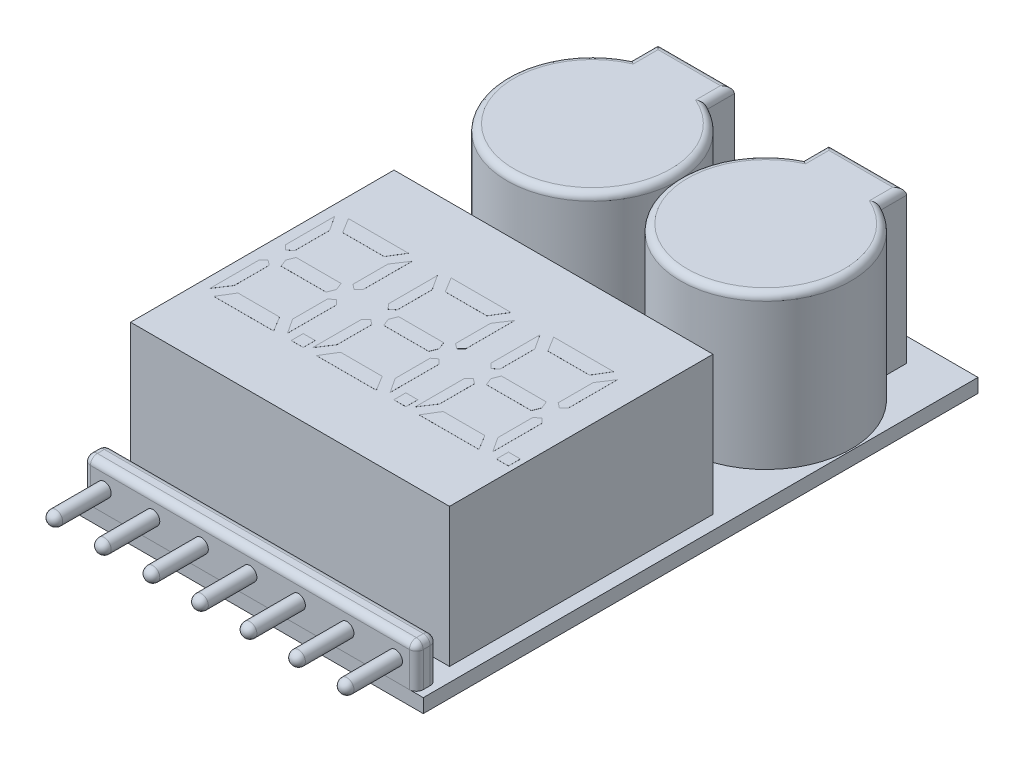
SolidWorks part; units mm, degrees
ref_plane "Ön Düzlem" through (0, 0, 0) normal (0, 0, 1) x (1, 0, 0)
ref_plane "Üst Düzlem" through (0, 0, 0) normal (0, 1, 0) x (1, 0, 0)
ref_plane "Sağ Düzlem" through (0, 0, 0) normal (1, 0, 0) x (0, 0, -1)
sketch "Çizim1" plane through (0, 0, 0) normal (0, 1, 0) x (1, 0, 0)
  line L1 (12.5, -20) -> (-12.5, -20)
  line L2 (12.5, -20) -> (12.5, 20)
  line L3 (12.5, 20) -> (-12.5, 20)
  line L4 (-12.5, -20) -> (-12.5, 20)
  line L5 (12.5, -20) -> (-12.5, 20) construction
  line L6 (12.5, 20) -> (-12.5, -20) construction
  point P0 (0, 0)
  dimension "D1" = 40
  dimension "D2" = 25
extrude "extruded boss" add sketch "Çizim1" along normal blind 1
sketch "Çizim2" plane through (0, 1, 0) normal (0, 1, 0) x (1, 0, 0)
  line L0 (-12.5, -20) -> (12.5, -20) construction
  line L1 (-12, -20) -> (12, -20)
  line L2 (-12, -20) -> (-12, -18.5)
  line L3 (-12, -18.5) -> (12, -18.5)
  line L4 (12, -20) -> (12, -18.5)
  line L5 (-12.5, 20) -> (-12.5, -20) construction
  line L6 (12.5, -20) -> (12.5, 20) construction
  dimension "D1" = 0.5
  dimension "D2" = 0.5
  dimension "D3" = 1.5
extrude "pin header" add sketch "Çizim2" along normal blind 3 separate body
sketch "Çizim3" plane through (0, 0, 20) normal (0, 0, 1) x (1, 0, 0)
  line L0 (-12, 2.5) -> (12, 2.5) construction
  line L1 (-12, 4) -> (-12, 1) construction
  line L2 (12, 4) -> (12, 1) construction
  line L3 (-8.5, 2.5) -> (15.5, 2.5) construction
  line L4 (-5, 2.5) -> (19, 2.5) construction
  line L5 (-1.5, 2.5) -> (22.5, 2.5) construction
  line L6 (-15.5, 2.5) -> (8.5, 2.5) construction
  line L7 (-19, 2.5) -> (5, 2.5) construction
  line L8 (-22.5, 2.5) -> (1.5, 2.5) construction
  circle A0 centre (0, 2.5) radius 0.5
  circle A1 centre (3.5, 2.5) radius 0.5
  circle A2 centre (7, 2.5) radius 0.5
  circle A3 centre (10.5, 2.5) radius 0.5
  circle A4 centre (-3.5, 2.5) radius 0.5
  circle A5 centre (-7, 2.5) radius 0.5
  circle A6 centre (-10.5, 2.5) radius 0.5
  dimension "D1" = 1
  dimension "D2" = 4
  dimension "D3" = 4
extrude "pins" add sketch "Çizim3" along normal blind 4
sketch "Çizim4" plane through (0, 1, 0) normal (0, 1, 0) x (1, 0, 0)
  line L1 (-11.5, -17.1093) -> (11.5, -17.1093)
  line L2 (-11.5, -17.1093) -> (-11.5, 1.8907)
  line L3 (-11.5, 1.8907) -> (11.5, 1.8907)
  line L4 (11.5, -17.1093) -> (11.5, 1.8907)
  line L5 (-11.5, -17.1093) -> (11.5, 1.8907) construction
  line L6 (-11.5, 1.8907) -> (11.5, -17.1093) construction
  point P0 (0, -7.6093)
  dimension "D1" = 19
  dimension "D2" = 23
extrude "display" add sketch "Çizim4" along normal blind 10
sketch "Çizim5" plane through (0, 1, 0) normal (0, 1, 0) x (1, 0, 0)
  line L7 (3.4483, 16.4277) -> (3.4483, 18.2977)
  line L9 (-9, 16.4539) -> (-9, 18.4278)
  line L10 (-9, 18.4278) -> (-3.5, 18.4278)
  line L11 (-3.5, 16.4539) -> (-3.5, 18.4278)
  line L14 (9.0517, 18.2977) -> (3.4483, 18.2977)
  line L15 (9.0517, 16.4277) -> (9.0517, 18.2977)
  arc A0 (-9, 16.4539) -> (-3.5, 16.4539) centre (-6.25, 10.9454) ccw
  arc A1 (3.4483, 16.4277) -> (9.0517, 16.4277) centre (6.25, 10.9454) ccw
  point P9 (0, 6.418)
  point P16 (-6.25, 17.1022)
  dimension "D1" = 5.5
extrude "buzzer" add sketch "Çizim5" along normal blind 11
fillet "fillet 1" radius 0.5 8 edges at (12, 4, 19.25) (0, 4, 20) (12, 2.5, 20) (-12, 4, 19.25) (-12, 2.5, 20) (-12, 2.5, 18.5) (0, 4, 18.5) (12, 2.5, 18.5)
fillet "fillet 2" radius 0.5 8 edges at (3.4483, 12, -17.3627) (6.25, 12, -18.2977) (9.0517, 12, -17.3627) (6.25, 12, -4.7885) (-9, 12, -17.4408) (-6.25, 12, -18.4278) (-3.5, 12, -17.4408) (-6.25, 12, -4.7885)
sketch "Çizim8" plane through (0, 11, 0) normal (0, 1, 0) x (1, 0, 0)
  line L0 (-9.5659, -7.1026) -> (-6.3259, -7.1026)
  line L1 (-6.4462, -11.4175) -> (-9.4456, -11.4175)
  line L2 (-9.4456, -11.4175) -> (-10.1059, -12.4975)
  line L3 (-10.048, -11.0796) -> (-10.743, -12.1376)
  line L4 (-10.743, -12.1376) -> (-10.743, -8.6075)
  line L5 (-10.048, -11.0796) -> (-10.048, -8.5587)
  line L6 (-10.743, -8.6075) -> (-10.4177, -8.2746)
  line L7 (-10.4177, -8.2746) -> (-10.048, -8.5587)
  line L8 (-9.5659, -8.1826) -> (-6.3259, -8.1826)
  line L9 (-10.1059, -12.4975) -> (-5.7859, -12.4975)
  line L10 (-4.559, -11.5993) -> (-3.695, -11.5993)
  line L11 (-4.559, -11.5993) -> (-4.559, -12.4633)
  line L12 (-4.559, -12.4633) -> (-3.695, -12.4633)
  line L13 (-9.7799, -7.6426) -> (-9.5659, -7.1026)
  line L14 (-3.695, -11.5993) -> (-3.695, -12.4633)
  line L15 (-6.112, -7.6426) -> (-6.3259, -7.1026)
  line L16 (-5.4741, -8.2746) -> (-5.8439, -8.5587)
  line L17 (-5.1489, -8.6075) -> (-5.4741, -8.2746)
  line L18 (-5.8439, -11.0796) -> (-5.8439, -8.5587)
  line L19 (-5.1489, -12.1376) -> (-5.1489, -8.6075)
  line L20 (-5.8439, -11.0796) -> (-5.1489, -12.1376)
  line L21 (-6.4462, -11.4175) -> (-5.7859, -12.4975)
  line L23 (-2.7059, -12.4975) -> (1.6141, -12.4975)
  line L24 (-5.7859, -2.7878) -> (-10.1059, -2.7878)
  line L25 (4.6941, -12.4975) -> (9.0141, -12.4975)
  line L26 (-9.4456, -3.8678) -> (-6.4462, -3.8678)
  line L27 (-6.4462, -3.8678) -> (-5.7859, -2.7878)
  line L28 (-5.8439, -4.2057) -> (-5.1489, -3.1477)
  line L29 (-5.1489, -3.1477) -> (-5.1489, -6.6778)
  line L30 (-5.8439, -4.2057) -> (-5.8439, -6.7266)
  line L31 (-5.1489, -6.6778) -> (-5.4741, -7.0107)
  line L32 (-5.4741, -7.0107) -> (-5.8439, -6.7266)
  line L33 (0.9538, -11.4175) -> (-2.0456, -11.4175)
  line L34 (-6.112, -7.6426) -> (-6.3259, -8.1826)
  line L35 (-9.7799, -7.6426) -> (-9.5659, -8.1826)
  line L36 (-2.0456, -11.4175) -> (-2.7059, -12.4975)
  line L37 (5.2341, -8.1826) -> (8.4741, -8.1826)
  line L38 (8.4741, -7.1026) -> (5.2341, -7.1026)
  line L39 (-10.4177, -7.0107) -> (-10.048, -6.7266)
  line L40 (-10.743, -6.6778) -> (-10.4177, -7.0107)
  line L41 (-10.048, -4.2057) -> (-10.048, -6.7266)
  line L42 (-10.743, -3.1477) -> (-10.743, -6.6778)
  line L43 (-10.048, -4.2057) -> (-10.743, -3.1477)
  line L44 (-9.4456, -3.8678) -> (-10.1059, -2.7878)
  line L46 (-2.648, -11.0796) -> (-3.343, -12.1376)
  line L48 (-3.343, -12.1376) -> (-3.343, -8.6075)
  line L49 (-2.648, -11.0796) -> (-2.648, -8.5587)
  line L50 (-3.343, -8.6075) -> (-3.0177, -8.2746)
  line L51 (-3.0177, -8.2746) -> (-2.648, -8.5587)
  line L52 (1.0741, -8.1826) -> (-2.1659, -8.1826)
  line L53 (-2.1659, -7.1026) -> (1.0741, -7.1026)
  line L54 (2.841, -11.5993) -> (3.705, -11.5993)
  line L55 (2.841, -11.5993) -> (2.841, -12.4633)
  line L56 (2.841, -12.4633) -> (3.705, -12.4633)
  line L57 (-2.3799, -7.6426) -> (-2.1659, -7.1026)
  line L58 (3.705, -11.5993) -> (3.705, -12.4633)
  line L59 (1.288, -7.6426) -> (1.0741, -7.1026)
  line L60 (1.9259, -8.2746) -> (1.5561, -8.5587)
  line L61 (2.2511, -8.6075) -> (1.9259, -8.2746)
  line L62 (1.5561, -11.0796) -> (1.5561, -8.5587)
  line L63 (2.2511, -12.1376) -> (2.2511, -8.6075)
  line L64 (1.5561, -11.0796) -> (2.2511, -12.1376)
  line L65 (0.9538, -11.4175) -> (1.6141, -12.4975)
  line L68 (1.6141, -2.7878) -> (-2.7059, -2.7878)
  line L69 (-2.0456, -3.8678) -> (0.9538, -3.8678)
  line L70 (0.9538, -3.8678) -> (1.6141, -2.7878)
  line L71 (1.5561, -4.2057) -> (2.2511, -3.1477)
  line L72 (2.2511, -3.1477) -> (2.2511, -6.6778)
  line L73 (1.5561, -4.2057) -> (1.5561, -6.7266)
  line L74 (2.2511, -6.6778) -> (1.9259, -7.0107)
  line L75 (1.9259, -7.0107) -> (1.5561, -6.7266)
  line L76 (1.288, -7.6426) -> (1.0741, -8.1826)
  line L77 (-2.3799, -7.6426) -> (-2.1659, -8.1826)
  line L80 (-3.0177, -7.0107) -> (-2.648, -6.7266)
  line L81 (-3.343, -6.6778) -> (-3.0177, -7.0107)
  line L82 (-2.648, -4.2057) -> (-2.648, -6.7266)
  line L83 (-3.343, -3.1477) -> (-3.343, -6.6778)
  line L84 (-2.648, -4.2057) -> (-3.343, -3.1477)
  line L85 (-2.0456, -3.8678) -> (-2.7059, -2.7878)
  line L88 (-11.5, 1.8907) -> (11.5, 1.8907) construction
  line L94 (8.3538, -11.4175) -> (5.3544, -11.4175)
  line L95 (5.3544, -11.4175) -> (4.6941, -12.4975)
  line L96 (4.752, -11.0796) -> (4.057, -12.1376)
  line L97 (4.057, -12.1376) -> (4.057, -8.6075)
  line L98 (4.752, -11.0796) -> (4.752, -8.5587)
  line L99 (4.057, -8.6075) -> (4.3823, -8.2746)
  line L100 (4.3823, -8.2746) -> (4.752, -8.5587)
  line L103 (10.241, -11.5993) -> (11.105, -11.5993)
  line L104 (10.241, -11.5993) -> (10.241, -12.4633)
  line L105 (10.241, -12.4633) -> (11.105, -12.4633)
  line L106 (5.0201, -7.6426) -> (5.2341, -7.1026)
  line L107 (11.105, -11.5993) -> (11.105, -12.4633)
  line L108 (8.688, -7.6426) -> (8.4741, -7.1026)
  line L109 (9.3259, -8.2746) -> (8.9561, -8.5587)
  line L110 (9.6511, -8.6075) -> (9.3259, -8.2746)
  line L111 (8.9561, -11.0796) -> (8.9561, -8.5587)
  line L112 (9.6511, -12.1376) -> (9.6511, -8.6075)
  line L113 (8.9561, -11.0796) -> (9.6511, -12.1376)
  line L114 (8.3538, -11.4175) -> (9.0141, -12.4975)
  line L117 (9.0141, -2.7878) -> (4.6941, -2.7878)
  line L118 (5.3544, -3.8678) -> (8.3538, -3.8678)
  line L119 (8.3538, -3.8678) -> (9.0141, -2.7878)
  line L120 (8.9561, -4.2057) -> (9.6511, -3.1477)
  line L121 (9.6511, -3.1477) -> (9.6511, -6.6778)
  line L122 (8.9561, -4.2057) -> (8.9561, -6.7266)
  line L123 (9.6511, -6.6778) -> (9.3259, -7.0107)
  line L124 (9.3259, -7.0107) -> (8.9561, -6.7266)
  line L125 (8.688, -7.6426) -> (8.4741, -8.1826)
  line L126 (5.0201, -7.6426) -> (5.2341, -8.1826)
  line L129 (4.3823, -7.0107) -> (4.752, -6.7266)
  line L130 (4.057, -6.6778) -> (4.3823, -7.0107)
  line L131 (4.752, -4.2057) -> (4.752, -6.7266)
  line L132 (4.057, -3.1477) -> (4.057, -6.6778)
  line L133 (4.752, -4.2057) -> (4.057, -3.1477)
  line L134 (5.3544, -3.8678) -> (4.6941, -2.7878)
  point P5 (6.7908, -7.6093)
  point P55 (-7.9459, -7.6093)
  point P80 (-0.5459, -7.6093)
  point P138 (6.8541, -7.6093)
  point P156 (15.105, -7.6093)
extrude "display numbers" add sketch "Çizim8" along normal blind 0.005 separate body
fillet "fillet 3" radius 0.5 7 edges at (7.5, 2.5, 24) (4, 2.5, 24) (0.5, 2.5, 24) (-3, 2.5, 24) (-6.5, 2.5, 24) (-10, 2.5, 24) (11, 2.5, 24)
